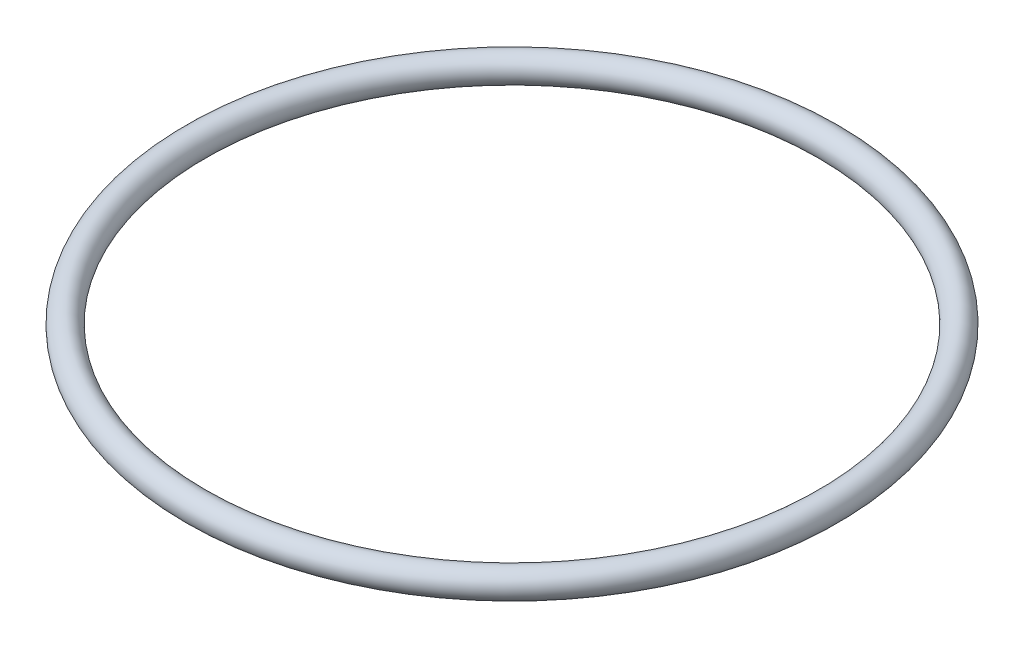
SolidWorks part; units mm, degrees
ref_plane "Front Plane" through (0, 0, 0) normal (0, 0, 1) x (1, 0, 0)
ref_plane "Top Plane" through (0, 0, 0) normal (0, 1, 0) x (1, 0, 0)
ref_plane "Right Plane" through (0, 0, 0) normal (1, 0, 0) x (0, 0, -1)
sketch "Sketch1" plane through (0, 0, 0) normal (0, 0, 1) x (1, 0, 0)
  line L0 (-37.103, 0) -> (0, 0) construction
  line L1 (0, 0) -> (0, 46.4972) construction
  circle A0 centre (-37.103, 0) radius 1.5875
  dimension "D1" = 3.175
  dimension "D2" = 37.103
revolve "Revolve1" add sketch "Sketch1" angle 360 about L1
sketch "Sketch3" plane through (0, 0, 0) normal (0, 0, 1) x (1, 0, 0)
  line L0 (0, 0) -> (0, 1.5875)
  dimension "D1" = 1.5875
